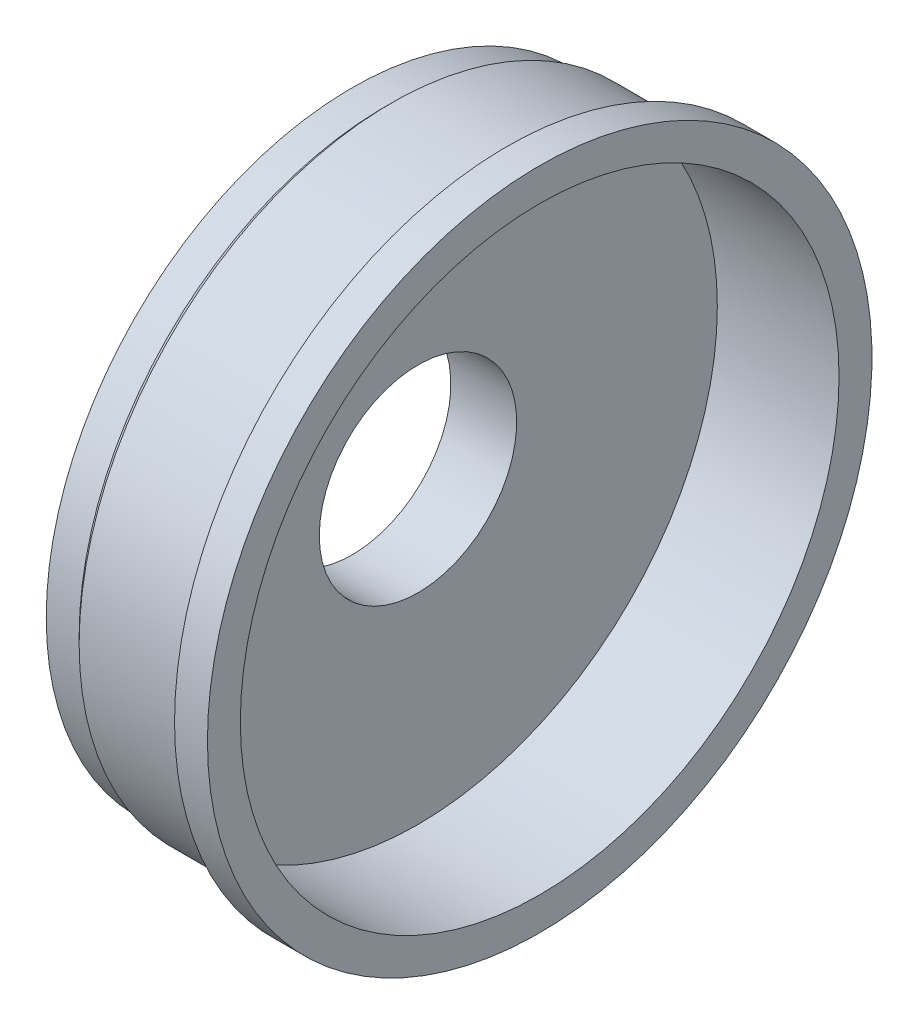
SolidWorks part; units mm, degrees
ref_plane "Front Plane" through (0, 0, 0) normal (0, 0, 1) x (1, 0, 0)
ref_plane "Top Plane" through (0, 0, 0) normal (0, 1, 0) x (1, 0, 0)
ref_plane "Right Plane" through (0, 0, 0) normal (1, 0, 0) x (0, 0, -1)
sketch "Sketch1" plane through (0, 0, 0) normal (0, 0, 1) x (1, 0, 0)
  line B0 (-14.9225, 9.525) -> (-8.5725, 9.525)
  line B1 (-8.5725, 9.525) -> (-8.5725, 28.8925)
  line B2 (3.175, 32.0675) -> (0, 32.0675)
  line B3 (0, 32.0675) -> (0, 30.1625)
  line B4 (0, 30.1625) -> (-11.1125, 30.1625)
  line B5 (-11.7475, 29.5275) -> (-11.1125, 30.1625)
  line B6 (-11.7475, 29.5275) -> (-14.9225, 29.5275)
  line B7 (-14.9225, 29.5275) -> (-14.9225, 9.525)
  line B8 (0, 0) -> (101.9592, 0) construction
  line B9 (-8.5725, 28.8925) -> (3.175, 28.8925)
  line B10 (3.175, 28.8925) -> (3.175, 32.0675)
sketch_block_instance "Block1-1"
sketch_block "Block1" parameters "D1"=3.175, "D2"=11.1125, "D3"=0.635, "D4"=45, "D5"=3.175, "D6"=19.05, "D7"=3.175, "D8"=6.35
revolve "Revolve1" add sketch "Sketch1" angle 360 about L8
